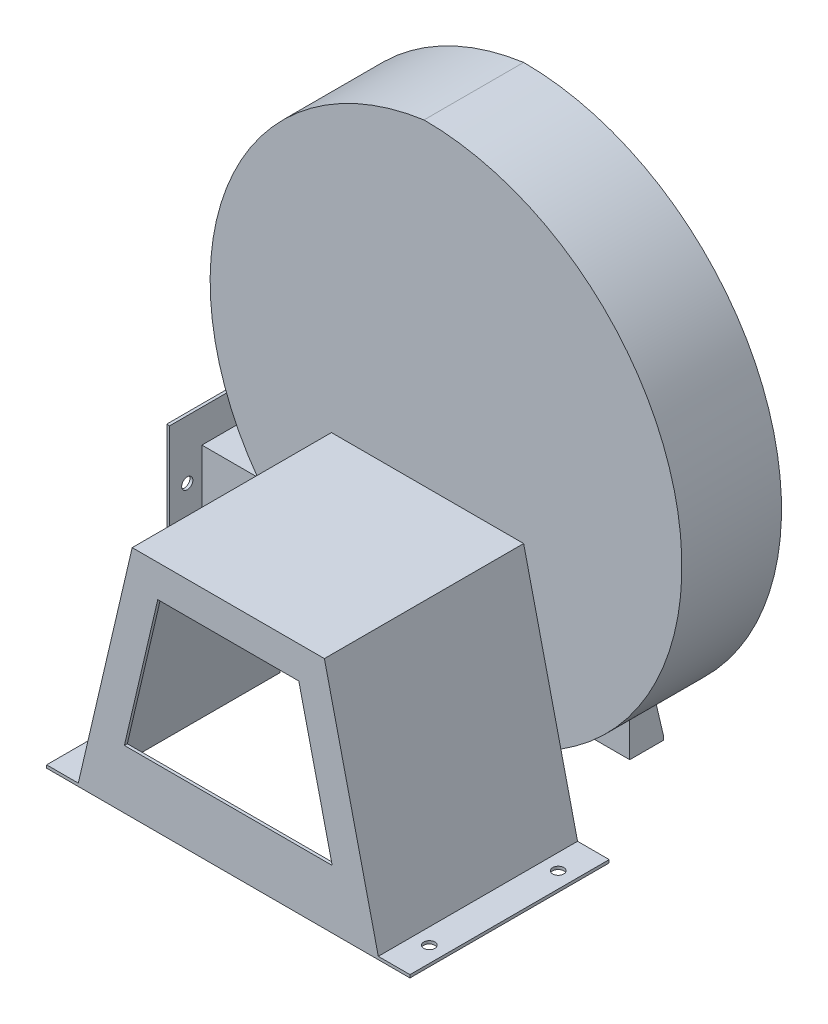
SolidWorks part; units mm, degrees
ref_plane "Alzado" through (0, 0, 0) normal (0, 0, 1) x (1, 0, 0)
ref_plane "Planta" through (0, 0, 0) normal (0, 1, 0) x (1, 0, 0)
ref_plane "Vista lateral" through (0, 0, 0) normal (1, 0, 0) x (0, 0, -1)
sketch "Croquis1" plane through (0, 0, 0) normal (0, 0, 1) x (1, 0, 0)
  line L0 (0, 0) -> (29, 0)
  line L1 (29, 0) -> (75, 197)
  line L2 (75, 197) -> (235, 197)
  line L3 (155, 197) -> (155, 0) construction
  line L4 (155, 0) -> (29, 0) construction
  line L5 (310, 0) -> (281, 0)
  line L6 (281, 0) -> (235, 197)
  line L7 (0, 2.5) -> (27.0165, 2.5)
  line L8 (27.0165, 2.5) -> (73.0165, 199.5)
  line L9 (73.0165, 199.5) -> (236.9835, 199.5)
  line L10 (282.9835, 2.5) -> (236.9835, 199.5)
  line L11 (310, 2.5) -> (282.9835, 2.5)
  line L12 (0, 2.5) -> (0, 0)
  line L13 (310, 2.5) -> (310, 0)
  dimension "D1" = 29
  dimension "D2" = 155
  dimension "D3" = 80
  dimension "D4" = 197
  dimension "D5" = 2.5
extrude "Saliente-Extruir1" add sketch "Croquis1" along normal blind 170
sketch "Croquis2" plane through (0, 0, 170) normal (0, 0, 1) x (1, 0, 0)
  line L0 (29, 0) -> (281, 0)
  line L1 (281, 0) -> (269.2863, 50.1652)
  line L2 (235, 197) -> (281, 0) construction
  line L3 (243.6524, 50) -> (66.3476, 50)
  line L4 (29, 0) -> (75, 197) construction
  line L5 (40.7137, 50.1652) -> (29, 0)
  line L6 (66.3476, 50) -> (94.8349, 172)
  line L7 (243.6524, 50) -> (215.1651, 172)
  line L8 (94.8349, 172) -> (215.1651, 172)
  line L9 (75, 197) -> (235, 197) construction
  line L10 (40.7137, 50.1652) -> (75, 197)
  line L11 (75, 197) -> (235, 197)
  line L12 (235, 197) -> (269.2863, 50.1652)
  dimension "D1" = 50
  dimension "D2" = 25
  dimension "D3" = 25
  dimension "D4" = 25
extrude "Saliente-Extruir2" add sketch "Croquis2" against normal blind 2.5
sketch "Croquis4" plane through (0, 2.5, 0) normal (0, 1, 0) x (1, 0, 0)
  line L0 (13.5083, 0) -> (13.5083, -170) construction
  line L1 (27.0165, 0) -> (0, 0) construction
  line L2 (27.0165, -170) -> (0, -170) construction
  line L3 (296.4917, 0) -> (296.4917, -170) construction
  line L4 (310, 0) -> (282.9835, 0) construction
  line L5 (310, -170) -> (282.9835, -170) construction
  line L6 (155, 0) -> (155, -170) construction
  line L7 (236.9835, 0) -> (73.0165, 0) construction
  line L8 (236.9835, -170) -> (73.0165, -170) construction
  circle A0 centre (13.5083, -30) radius 4.7625
  circle A1 centre (13.5083, -140) radius 4.7625
  circle A2 centre (296.4917, -140) radius 4.7625
  circle A3 centre (296.4917, -30) radius 4.7625
  dimension "D1" = 9.525
  dimension "D2" = 9.525
  dimension "D4" = 30
  dimension "D3" = 30
extrude "Cortar-Extruir1" cut sketch "Croquis4" against normal blind 2.5
sketch "Croquis5" plane through (0, 0, 0) normal (0, 0, -1) x (-1, 0, 0)
  line L0 (-281, 0) -> (-152, 0) construction
  line L1 (-152, 0) -> (-152, 470) construction
  line L2 (-29, 0) -> (-281, 0) construction
  line L3 (0, 30) -> (40, 30)
  line L4 (-152, 30) -> (0, 30)
  line L5 (0, 30) -> (0, 0) construction
  line L6 (40, 30) -> (40, 135)
  line L7 (40, 135) -> (-10, 135)
  arc A0 (-152, 470) -> (-152, 30) centre (-152, 250) ccw
  arc A1 (-152, 470) -> (-10, 135) centre (-181.8777, 259.7399) cw
  dimension "D1" = 470
  dimension "D2" = 30
  dimension "D3" = 40
  dimension "D4" = 105
  dimension "D5" = 50
  dimension "D6" = 152
extrude "Saliente-Extruir3" add sketch "Croquis5" along normal blind 2.5
sketch "Croquis6" plane through (0, 0, -2.5) normal (0, 0, -1) x (-1, 0, 0)
  line L0 (-10, 135) -> (40, 135)
  line L1 (40, 135) -> (40, 133)
  line L2 (40, 30) -> (-152, 30)
  line L3 (38, 32) -> (-152, 32)
  line L4 (-13.9685, 133) -> (38, 133)
  line L6 (38, 32) -> (40, 32)
  line L7 (38, 133) -> (40, 133)
  line L8 (40, 32) -> (40, 30)
  line L9 (40, 135) -> (40, 30) construction
  line L10 (38, 133) -> (38, 32) construction
  arc A0 (-152, 470) -> (-152, 30) centre (-152, 250) ccw
  arc A1 (-152, 470) -> (-152, 30) centre (-152, 250) ccw construction
  arc A2 (-152, 470) -> (-10, 135) centre (-181.8777, 259.7399) cw
  arc A3 (-152.1414, 468) -> (-152, 32) centre (-152, 250) ccw
  arc A4 (-152.1414, 468) -> (-13.9685, 133) centre (-181.8777, 259.7399) cw
  dimension "D1" = 2
extrude "Saliente-Extruir4" add sketch "Croquis6" along normal blind 80
sketch "Croquis7" plane through (0, 0, -82.5) normal (0, 0, -1) x (-1, 0, 0)
  line L0 (-10, 135) -> (40, 135)
  line L1 (40, 135) -> (40, 30)
  line L2 (40, 30) -> (-152, 30)
  arc A0 (-152, 470) -> (-152, 30) centre (-152, 250) ccw
  arc A1 (-152, 470) -> (-152, 30) centre (-152, 250) ccw construction
  arc A2 (-152, 470) -> (-10, 135) centre (-181.8777, 259.7399) cw
extrude "Saliente-Extruir5" add sketch "Croquis7" along normal blind 2.5
sketch "Croquis8" plane through (-40, 0, 0) normal (-1, 0, 0) x (0, 0, 1)
  line L0 (-112.5, 163) -> (-112.5, 2)
  line L1 (-82.5, 133) -> (-2.5, 133)
  line L2 (-82.5, 133) -> (-82.5, 32)
  line L3 (-82.5, 32) -> (-2.5, 32)
  line L4 (-2.5, 133) -> (-2.5, 32)
  line L5 (-112.5, 2) -> (27.5, 2)
  line L6 (27.5, 163) -> (27.5, 2)
  line L7 (-112.5, 163) -> (27.5, 163)
  dimension "D1" = 30
extrude "Saliente-Extruir6" add sketch "Croquis8" against normal blind 2.5
sketch "Croquis9" plane through (-40, 0, 0) normal (-1, 0, 0) x (0, 0, 1)
  line L0 (-42.5, 133) -> (-42.5, 163) construction
  line L1 (-82.5, 133) -> (-2.5, 133) construction
  line L2 (27.5, 163) -> (-112.5, 163) construction
  line L3 (-82.5, 82.5) -> (-112.5, 82.5) construction
  line L4 (-82.5, 32) -> (-82.5, 133) construction
  line L5 (-112.5, 163) -> (-112.5, 2) construction
  line L6 (-97.5, 82.5) -> (-97.5, 163) construction
  line L7 (-2.5, 82.5) -> (27.5, 82.5) construction
  line L8 (-2.5, 32) -> (-2.5, 133) construction
  line L9 (27.5, 2) -> (27.5, 163) construction
  line L10 (12.5, 82.5) -> (12.5, 163) construction
  line L11 (-42.5, 32) -> (-42.5, 2) construction
  circle A0 centre (-42.5, 148) radius 4.7625
  circle A1 centre (-97.5, 113) radius 4.7625
  circle A2 centre (12.5, 113) radius 4.7625
  circle A3 centre (12.5, 52) radius 4.7625
  circle A4 centre (-97.5, 52) radius 4.7625
  circle A5 centre (-42.5, 17) radius 4.7625
  dimension "D1" = 9.525
  dimension "D3" = 9.525
  dimension "D4" = 9.525
  dimension "D5" = 50
  dimension "D2" = 50
extrude "Cortar-Extruir2" cut sketch "Croquis9" against normal blind 2.5
sketch "Croquis10" plane through (0, 0, -85) normal (0, 0, -1) x (-1, 0, 0)
  line L0 (-155, 199.5) -> (-155, 279.5) construction
  line L1 (-236.9835, 199.5) -> (-73.0165, 199.5) construction
  circle A0 centre (-155, 279.5) radius 61
  dimension "D2" = 122
  dimension "D1" = 80
extrude "Cortar-Extruir3" cut sketch "Croquis10" against normal blind 2.5
sketch "Croquis11" plane through (0, 0, -85) normal (0, 0, -1) x (-1, 0, 0)
  circle A0 centre (-155, 279.5) radius 61
  circle A1 centre (-155, 279.5) radius 63.5
  dimension "D1" = 2.5
extrude "Saliente-Extruir7" add sketch "Croquis11" along normal blind 28.5
sketch "Croquis12" plane through (0, 0, -113.5) normal (0, 0, -1) x (-1, 0, 0)
  line L0 (-155, 340.5) -> (-155, 367.5) construction
  circle A0 centre (-155, 279.5) radius 61
  circle A1 centre (-155, 279.5) radius 88
  dimension "D1" = 27
extrude "Saliente-Extruir8" add sketch "Croquis12" against normal blind 2.5
sketch "Croquis13" plane through (0, 0, -85) normal (0, 0, -1) x (-1, 0, 0)
  line L0 (-155, 0) -> (-155, 115) construction
  line L1 (-29, 0) -> (-281, 0) construction
  line L3 (-242.5, 0) -> (-67.5, 0)
  line L4 (-242.5, 0) -> (-242.5, 115)
  line L5 (-242.5, 115) -> (-67.5, 115)
  line L6 (-67.5, 0) -> (-67.5, 115)
  line L7 (-242.5, 0) -> (-67.5, 115) construction
  line L8 (-242.5, 115) -> (-67.5, 0) construction
  point P4 (-155, 57.5)
  dimension "D1" = 115
  dimension "D2" = 175
extrude "Saliente-Extruir9" add sketch "Croquis13" along normal blind 2.5
sketch "Croquis14" plane through (0, 0, -87.5) normal (0, 0, -1) x (-1, 0, 0)
  line L0 (-67.5, 0) -> (-67.5, 115) construction
  line L1 (-242.5, 0) -> (-67.5, 0)
  line L2 (-242.5, 0) -> (-242.5, 2.5)
  line L3 (-242.5, 2.5) -> (-67.5, 2.5)
  line L4 (-67.5, 0) -> (-67.5, 2.5)
  dimension "D1" = 2.5
extrude "Saliente-Extruir10" add sketch "Croquis14" along normal blind 26.5
sketch "Croquis15" plane through (67.5, 0, 0) normal (-1, 0, 0) x (0, 0, 1)
  line L0 (-114, 2.5) -> (-87.5, 115)
  line L1 (-87.5, 115) -> (-85, 115)
  line L2 (-85, 115) -> (-85, 0)
  line L3 (-85, 0) -> (-114, 0)
  line L4 (-114, 0) -> (-114, 2.5)
extrude "Saliente-Extruir11" add sketch "Croquis15" against normal blind 2.5
sketch "Croquis16" plane through (242.5, 0, 0) normal (1, 0, 0) x (0, 0, -1)
  line L0 (114, 2.5) -> (87.5, 115)
  line L1 (87.5, 115) -> (85, 115)
  line L2 (85, 115) -> (85, 0)
  line L3 (85, 0) -> (114, 0)
  line L4 (114, 0) -> (114, 2.5)
extrude "Saliente-Extruir12" add sketch "Croquis16" against normal blind 2.5
sketch "Croquis17" plane through (0, 0, 0) normal (0, -1, 0) x (1, 0, 0)
  line L0 (240, -100.75) -> (70, -100.75) construction
  line L1 (240, -114) -> (240, -87.5) construction
  line L2 (70, -114) -> (70, -87.5) construction
  line L3 (242.5, -114) -> (242.5, -85) construction
  line L4 (67.5, -114) -> (67.5, -85) construction
  circle A0 centre (198.5, -100.75) radius 4.7625
  circle A1 centre (111.5, -100.75) radius 4.7625
  dimension "D1" = 9.525
  dimension "D2" = 9.525
  dimension "D3" = 44
  dimension "D4" = 44
extrude "Cortar-Extruir4" cut sketch "Croquis17" against normal blind 2.5
sketch "Croquis18" plane through (0, 0, -85) normal (0, 0, -1) x (-1, 0, 0)
  circle A0 centre (-155, 279.5) radius 154
  dimension "D1" = 308
extrude "Saliente-Extruir13" add sketch "Croquis18" along normal blind 2.5
sketch "Croquis19" plane through (0, 0, -87.5) normal (0, 0, -1) x (-1, 0, 0)
  line L0 (-1, 279.5) -> (-13, 279.5) construction
  circle A0 centre (-155, 279.5) radius 154 construction
  circle A1 centre (-13, 279.5) radius 3.9688
  dimension "D2" = 7.9375
  dimension "D1" = 12
extrude "Saliente-Extruir14" add sketch "Croquis19" along normal blind 16
pattern_circular "MatrizC1" count 6 every 60 about axis through (155, 279.5, 0) along (0, 0, 1) of "Saliente-Extruir14"
sketch "Croquis20" plane through (0, 0, -87.5) normal (0, 0, -1) x (-1, 0, 0)
  line L1 (-6.0718, 279.5) -> (-9.5359, 285.5)
  line L2 (-9.5359, 285.5) -> (-16.4641, 285.5)
  line L3 (-16.4641, 285.5) -> (-19.9282, 279.5)
  line L4 (-19.9282, 279.5) -> (-16.4641, 273.5)
  line L5 (-16.4641, 273.5) -> (-9.5359, 273.5)
  line L6 (-9.5359, 273.5) -> (-6.0718, 279.5)
  circle A0 centre (-13, 279.5) radius 3.9688
  circle A1 centre (-13, 279.5) radius 6 construction
  dimension "D1" = 12
extrude "Saliente-Extruir15" add sketch "Croquis20" along normal blind 7
pattern_circular "MatrizC3" count 6 every 60 about axis through (155, 279.5, 0) along (0, 0, 1) of "Saliente-Extruir15"
scale "Escala1" scale about centroid uniform scaling yes scale factor 2
